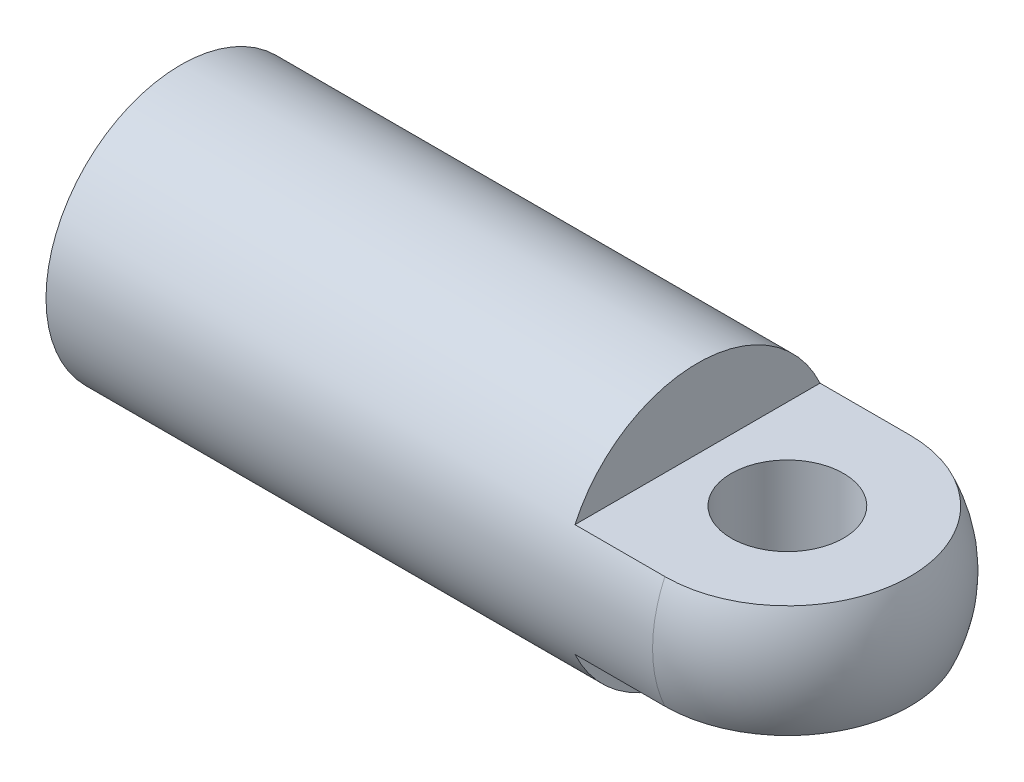
SolidWorks part; units mm, degrees
ref_plane "Front Plane" through (0, 0, 0) normal (0, 0, 1) x (1, 0, 0)
ref_plane "Top Plane" through (0, 0, 0) normal (0, 1, 0) x (1, 0, 0)
ref_plane "Right Plane" through (0, 0, 0) normal (1, 0, 0) x (0, 0, -1)
sketch "Sketch1" plane through (0, 0, 0) normal (0, 1, 0) x (1, 0, 0)
  line L0 (-212.8571, 80) -> (-232.8571, 80)
  line L1 (-232.8571, 80) -> (-232.8571, 120)
  line L2 (-232.8571, 120) -> (307.1429, 120)
  line L3 (-212.8571, 80) -> (-212.8571, 100)
  line L4 (-212.8571, 100) -> (187.1429, 100)
  line L5 (187.1429, 100) -> (187.1429, 0)
  line L6 (307.1429, 0) -> (187.1429, 0)
  line L7 (427.1429, 0) -> (307.1429, 0)
  line L8 (-156.2927, 0) -> (142.5522, 0) construction
  arc A0 (307.1429, 120) -> (427.1429, 0) centre (307.1429, 0) cw
  point P12 (-212.8571, 90)
  dimension "D2" = 120
  dimension "D3" = 20
  dimension "D4" = 20
  dimension "D5" = 80
  dimension "D1" = 120
  dimension "D6" = 400
revolve "Revolve1" add sketch "Sketch1" angle 360 about L8
sketch "Sketch2" plane through (0, 0, 0) normal (0, 0, 1) x (1, 0, 0)
  line L1 (525.4041, 50) -> (227.1429, 50)
  line L2 (525.4041, 50) -> (525.4041, -50)
  line L3 (525.4041, -50) -> (227.1429, -50)
  line L5 (388.5821, 0) -> (0, 0) construction
  line L6 (227.1429, 50) -> (227.1429, 120)
  line L7 (227.1429, 120) -> (587.9488, 120)
  line L8 (587.9488, 120) -> (587.9488, -120)
  line L9 (587.9488, -120) -> (227.1429, -120)
  line L10 (227.1429, -120) -> (227.1429, -50)
  line L12 (-232.8571, 120) -> (-232.8571, -120) construction
  point P14 (0, 0)
  point P15 (0, 0)
  dimension "D1" = 50
  dimension "D3" = 460
  dimension "D4" = 460
extrude "Cut-Extrude2" cut sketch "Sketch2" against normal through all both and the other way through all
sketch "Sketch3" plane through (0, 50, 0) normal (0, 1, 0) x (1, 0, 0)
  circle A0 centre (307.1429, 0) radius 50
  dimension "D1" = 100
extrude "Cut-Extrude3" cut sketch "Sketch3" against normal through all both and the other way through all
equation "\"piston_external_radius\"= \"piston_internal_radius\" + 2 * \"piston_thickness\""
equation "\"piston_bottom_thickness\"= 120"
equation "\"piston_thickness\"=20"
equation "\"D3@Sketch1\"=\"piston_thickness\""
equation "\"piston_internal_radius\"=80"
equation "\"D5@Sketch1\"=\"piston_internal_radius\""
equation "\"D1@Sketch1\"=\"piston_external_radius\""
equation "\"pivot_thickness\" = 100"
equation "\"D1@Sketch2\"= \"pivot_thickness\" / 2"
equation "\"piston_travel\"= 400"
equation "\"D6@Sketch1\"=\"piston_travel\""
equation "\"D2@Sketch1\"=\"piston_bottom_thickness\""
equation "\"D3@Sketch2\"= \"piston_travel\" + \"piston_bottom_thickness\" / 2"
equation "\"D4@Sketch2\"=\"piston_travel\"+\"piston_bottom_thickness\"/2"
equation "\"pivot_diameter\"= 100"
equation "\"D1@Sketch3\"=\"pivot_diameter\""
